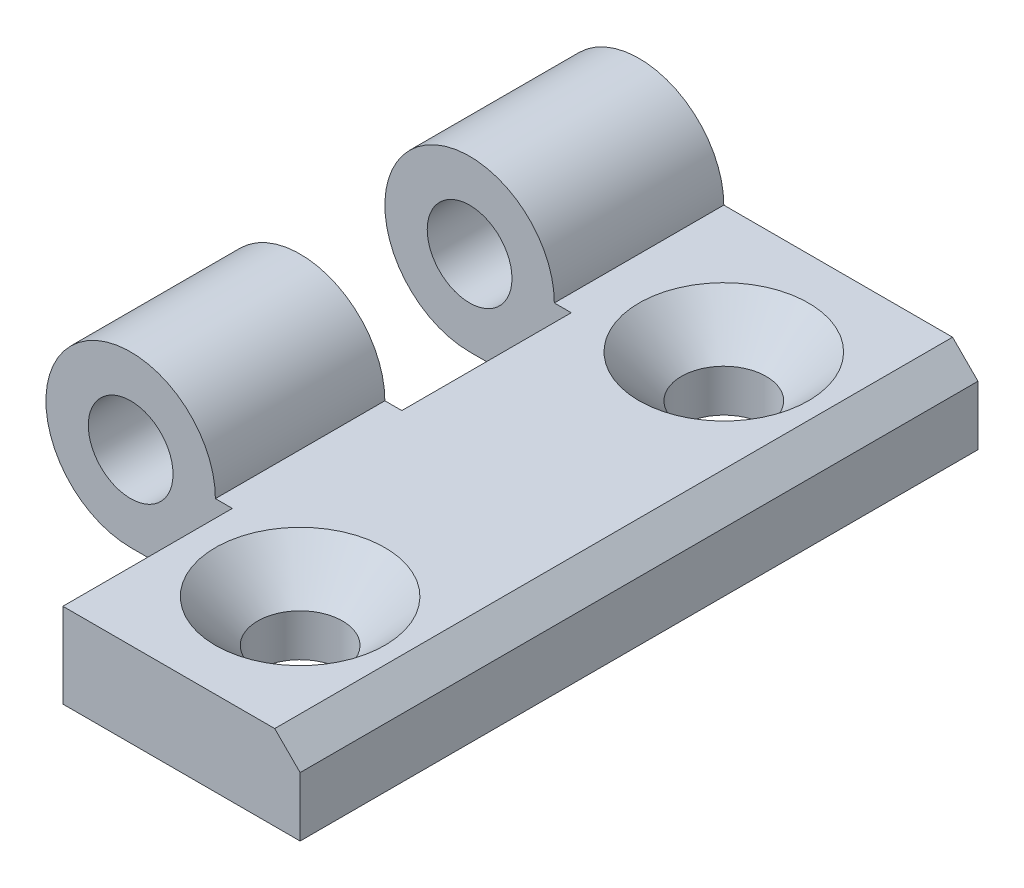
SolidWorks part; units mm, degrees
ref_plane "前视基准面" through (0, 0, 0) normal (0, 0, 1) x (1, 0, 0)
ref_plane "上视基准面" through (0, 0, 0) normal (0, 1, 0) x (1, 0, 0)
ref_plane "右视基准面" through (0, 0, 0) normal (1, 0, 0) x (0, 0, -1)
sketch "草图1" plane through (0, 0, 0) normal (0, 0, 1) x (1, 0, 0)
  line L1 (-7, 2.5) -> (7, 2.5)
  line L2 (-7, 2.5) -> (-7, -2.5)
  line L3 (-7, -2.5) -> (7, -2.5)
  line L4 (7, 2.5) -> (7, -2.5)
  line L5 (-7, 2.5) -> (7, -2.5) construction
  line L6 (-7, -2.5) -> (7, 2.5) construction
  point P0 (0, 0)
extrude "凸台-拉伸1" add sketch "草图1" along normal blind 40
sketch "草图3" plane through (0, 0, 0) normal (0, 0, -1) x (-1, 0, 0)
  line L0 (-7, 2.5) -> (13, 2.5) construction
  line L1 (8, 2.5) -> (7, 2.5)
  line L2 (13, -2.5) -> (7, -2.5)
  line L3 (7, -2.5) -> (7, 2.5)
  circle A0 centre (13, 2.5) radius 5
  circle A1 centre (13, 2.5) radius 2.5
extrude "凸台-拉伸2" add sketch "草图3" against normal blind 40
sketch "草图4" plane through (0, 0, 40) normal (0, 0, 1) x (1, 0, 0)
  line L0 (-8, 2.5) -> (-7, 2.5) construction
  line L1 (7, 2.5) -> (-8, 2.5) construction
  line L2 (-7, 2.5) -> (-7, 10.8677)
  line L3 (-7, 10.8677) -> (-20.0639, 10.8677)
  line L4 (-20.0639, 10.8677) -> (-20.0639, -3.9342)
  line L5 (-20.0639, -3.9342) -> (-7, -3.9342)
  line L6 (-7, -3.9342) -> (-7, 2.5)
extrude "切除-拉伸1" cut sketch "草图4" against normal blind 10
pattern_linear "阵列(线性)1" count 2 spacing 20 along (0, 0, -1) of "切除-拉伸1"
hole_wizard "打孔尺寸(%根据十字)槽半沉头木螺钉的类型1" positions "草图6" profile "草图5" countersink size "M5" standard "GB" end condition through all
sketch "草图6" plane through (0, 2.5, 0) normal (0, 1, 0) x (1, 0, 0)
  line L0 (-0.5, -40) -> (-0.5, -32.5)
  line L1 (7, -40) -> (-7, -40) construction
  line L2 (-0.5, -32.5) -> (7, -32.5)
  line L3 (7, -40) -> (7, 0) construction
  line L5 (-0.5, 0) -> (-0.5, -7.5)
  line L6 (7, 0) -> (-8, 0) construction
  point P2 (-0.5, -32.5)
  point P11 (-0.5, -7.5)
sketch "草图5" plane through (-0.5, 2.5, 32.5) normal (1, 0, 0) x (0, 0, 1)
  line L0 (0, 0) -> (0, 5)
  line L1 (0, 5) -> (2.5, 5)
  line L2 (2.5, 5) -> (2.5, 2.5)
  line L3 (2.5, 2.5) -> (5, 0)
  line L5 (5, 0) -> (0, 0)
  line L6 (-2.5, 2.5) -> (-5, 0) construction
  line L11 (0, -6.35) -> (0, 107.95) construction
  dimension "通孔孔直径" = 5
  dimension "通孔孔深度" = 5
  dimension "近端锥形沉头孔直径" = 10
  dimension "近端锥形沉头孔角度" = 90
chamfer "倒角2" distance 1.5 angle 45 1 edges at (7, 2.5, 20)
